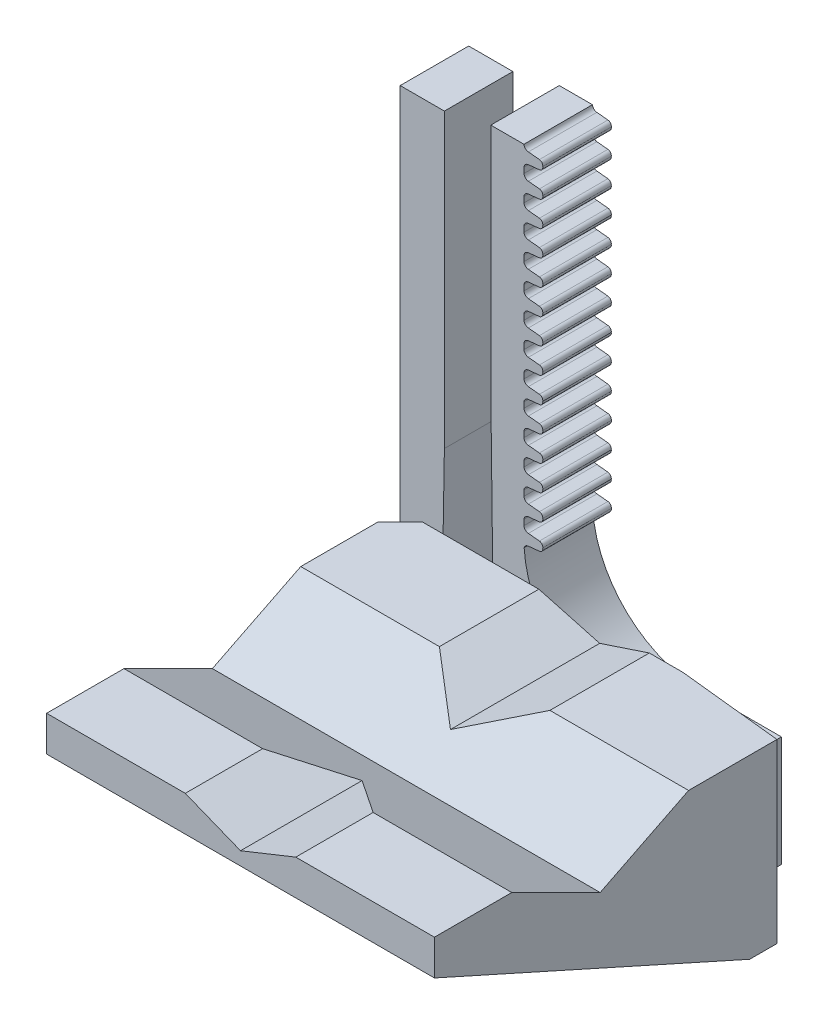
SolidWorks part; units mm, degrees
ref_plane "Front Plane" through (0, 0, 0) normal (0, 0, 1) x (1, 0, 0)
ref_plane "Top Plane" through (0, 0, 0) normal (0, 1, 0) x (1, 0, 0)
ref_plane "Right Plane" through (0, 0, 0) normal (1, 0, 0) x (0, 0, -1)
sketch "Sketch1" plane through (0, 0, 0) normal (0, 0, 1) x (1, 0, 0)
  line L1 (-28.3, 0) -> (0, 0)
  line L6 (-17.1, 20) -> (-17.1, 51)
  line L7 (-17.1, 51) -> (-20.1, 51)
  line L9 (0, 10) -> (-7.1, 10)
  line L11 (-20.1, 51) -> (-20.1, 6)
  line L12 (-28.3, 0) -> (-28.3, 50)
  line L13 (-28.3, 50) -> (-24.3, 50)
  line L14 (-24.3, 50) -> (-24.3, 6)
  line L15 (-24.3, 6) -> (-20.1, 6)
  line L16 (0, 10) -> (0, 0)
  arc A1 (-17.1, 20) -> (-7.1, 10) centre (-7.1, 20) ccw
  dimension "D8" = 10
  dimension "D1" = 45
  dimension "D2" = 4.2
  dimension "D3" = 3
  dimension "D4" = 17.1
  dimension "D5" = 50
  dimension "D6" = 6
  dimension "D7" = 10
  dimension "D9" = 4
extrude "Boss-Extrude1" add sketch "Sketch1" along normal blind 6.2
sketch "Sketch2" plane through (0, 0, 0) normal (0, -1, 0) x (1, 0, 0)
  line L0 (0, 6.2) -> (0, 10.4)
  line L1 (0, 10.4) -> (11, 10.4)
  line L2 (11, 10.4) -> (11, 42.4)
  line L3 (11, 42.4) -> (-24.1, 42.4)
  line L4 (-24.1, 42.4) -> (-24.1, 10.4)
  line L5 (-24.1, 10.4) -> (-13.1, 10.4)
  line L6 (-13.1, 10.4) -> (-13.1, 6.2)
  line L7 (-28.3, 6.2) -> (0, 6.2) construction
  line L8 (-13.1, 6.2) -> (0, 6.2)
  dimension "D1" = 4.2
  dimension "D2" = 7
  dimension "D3" = 11
  dimension "D4" = 11
  dimension "D5" = 32
extrude "Boss-Extrude2" add sketch "Sketch2" against normal blind 21
chamfer "Chamfer1" distance 5 angle 80 1 edges at (-6.55, 0, 42.4)
sketch "Sketch3" plane through (0, 0, 0) normal (1, 0, 0) x (0, 0, -1)
  line L0 (-6.2, 10) -> (-7.6, 10)
  line L1 (-7.6, 10) -> (-10.4, 21)
  line L2 (-10.4, 21) -> (-6.2, 21)
  line L3 (-6.2, 21) -> (-6.2, 10)
  dimension "D1" = 1.4
extrude "Cut-Extrude1" cut sketch "Sketch3" against normal up to next
chamfer "Chamfer2" distance 1 angle 84 1 edges at (11, 10.5, 10.4)
chamfer "Chamfer3" distance 2 angle 45 1 edges at (-24.1, 10.5, 10.4)
sketch "Sketch5" plane through (11, 0, 0) normal (1, 0, 0) x (0, 0, -1)
  line L0 (-42.4, 17.8) -> (-13.8689, 5)
  line L1 (-42.4, 21) -> (-42.4, 5) construction
  line L3 (-13.8689, 5) -> (-10.9662, -4.1087)
  line L4 (-10.9662, -4.1087) -> (-44.0369, 0.9377)
  line L5 (-44.0369, 0.9377) -> (-42.4, 17.8)
  line L6 (-11.4, 21) -> (-10.4, 21) construction
  dimension "D1" = 3.2
  dimension "D2" = 16
extrude "Cut-Extrude2" cut sketch "Sketch5" against normal up to next
sketch "Sketch6" plane through (0, 0, 10.4) normal (0, 0, -1) x (-1, 0, 0)
  line L0 (13.1, 0) -> (24.1, 5)
  line L1 (24.1, 5) -> (37.1983, 5)
  line L3 (-20.705, 5) -> (-11, 5)
  line L4 (-11, 5) -> (0, 0)
  line L5 (0, 0) -> (13.1, 0)
  line L6 (37.1983, 5) -> (28.626, -4.5222)
  line L7 (28.626, -4.5222) -> (-13.826, -5.6293)
  line L8 (-13.826, -5.6293) -> (-20.705, 5)
extrude "Cut-Extrude3" cut sketch "Sketch6" against normal up to next
sketch "Sketch7" plane through (0, 0, 6.2) normal (0, 0, 1) x (1, 0, 0)
  line L0 (-17.1, 20) -> (-17.1, 51) construction
  line L1 (-15.4, 50.1) -> (-17.4129, 50.1) construction
  line L2 (-16.7, 50.6) -> (-15.7, 50.5)
  line L3 (-16.7, 49.6) -> (-15.7, 49.7)
  line L4 (-17.1, 49.2) -> (-17.1, 48.7)
  line L5 (-16.7, 48.3) -> (-15.7, 48.2)
  line L6 (-16.7, 47.3) -> (-15.7, 47.4)
  line L7 (-17.1, 46.9) -> (-17.1, 46.4)
  line L8 (-16.7, 46) -> (-15.7, 45.9)
  line L9 (-16.7, 45) -> (-15.7, 45.1)
  line L10 (-17.1, 44.6) -> (-17.1, 44.1)
  line L11 (-16.7, 43.7) -> (-15.7, 43.6)
  line L12 (-16.7, 42.7) -> (-15.7, 42.8)
  line L13 (-17.1, 42.3) -> (-17.1, 41.8)
  line L14 (-16.7, 41.4) -> (-15.7, 41.3)
  line L15 (-16.7, 40.4) -> (-15.7, 40.5)
  line L16 (-17.1, 40) -> (-17.1, 39.5)
  line L17 (-16.7, 39.1) -> (-15.7, 39)
  line L18 (-16.7, 38.1) -> (-15.7, 38.2)
  line L19 (-17.1, 37.7) -> (-17.1, 37.2)
  line L20 (-16.7, 36.8) -> (-15.7, 36.7)
  line L21 (-16.7, 35.8) -> (-15.7, 35.9)
  line L22 (-17.1, 35.4) -> (-17.1, 34.9)
  line L23 (-16.7, 34.5) -> (-15.7, 34.4)
  line L24 (-16.7, 33.5) -> (-15.7, 33.6)
  line L25 (-17.1, 33.1) -> (-17.1, 32.6)
  line L26 (-16.7, 32.2) -> (-15.7, 32.1)
  line L27 (-16.7, 31.2) -> (-15.7, 31.3)
  line L28 (-17.1, 30.8) -> (-17.1, 30.3)
  line L29 (-16.7, 29.9) -> (-15.7, 29.8)
  line L30 (-16.7, 28.9) -> (-15.7, 29)
  line L31 (-17.1, 28.5) -> (-17.1, 28)
  line L32 (-16.7, 27.6) -> (-15.7, 27.5)
  line L33 (-16.7, 26.6) -> (-15.7, 26.7)
  line L34 (-17.1, 26.2) -> (-17.1, 25.7)
  line L35 (-16.7, 25.3) -> (-15.7, 25.2)
  line L36 (-16.7, 24.3) -> (-15.7, 24.4)
  line L37 (-17.1, 23.9) -> (-17.1, 23.4)
  line L38 (-16.7, 23) -> (-15.7, 22.9)
  line L39 (-16.7, 22) -> (-15.7, 22.1)
  line L40 (-17.1, 21.6) -> (-17.1, 21.1)
  line L41 (-16.7, 20.7) -> (-15.7, 20.6)
  line L42 (-16.7, 19.7) -> (-15.7, 19.8)
  line L43 (-17.1, 19.3) -> (-17.1, 18.8)
  line L44 (-17.1, 18.8) -> (-18.685, 49.2)
  line L45 (-18.685, 49.2) -> (-17.1, 51)
  arc A0 (-17.1, 51) -> (-16.7, 50.6) centre (-16.6556, 51.0444) ccw
  arc A1 (-15.7, 50.5) -> (-15.4, 50.1) centre (-15.7338, 50.1622) cw
  arc A2 (-17.1, 49.2) -> (-16.7, 49.6) centre (-16.6556, 49.1556) cw
  arc A3 (-15.7, 49.7) -> (-15.4, 50.1) centre (-15.7338, 50.0378) ccw
  arc A4 (-17.1, 48.7) -> (-16.7, 48.3) centre (-16.6556, 48.7444) ccw
  arc A5 (-15.7, 48.2) -> (-15.4, 47.8) centre (-15.7338, 47.8622) cw
  arc A6 (-17.1, 46.9) -> (-16.7, 47.3) centre (-16.6556, 46.8556) cw
  arc A7 (-15.7, 47.4) -> (-15.4, 47.8) centre (-15.7338, 47.7378) ccw
  arc A8 (-17.1, 46.4) -> (-16.7, 46) centre (-16.6556, 46.4444) ccw
  arc A9 (-15.7, 45.9) -> (-15.4, 45.5) centre (-15.7338, 45.5622) cw
  arc A10 (-17.1, 44.6) -> (-16.7, 45) centre (-16.6556, 44.5556) cw
  arc A11 (-15.7, 45.1) -> (-15.4, 45.5) centre (-15.7338, 45.4378) ccw
  arc A12 (-17.1, 44.1) -> (-16.7, 43.7) centre (-16.6556, 44.1444) ccw
  arc A13 (-15.7, 43.6) -> (-15.4, 43.2) centre (-15.7338, 43.2622) cw
  arc A14 (-17.1, 42.3) -> (-16.7, 42.7) centre (-16.6556, 42.2556) cw
  arc A15 (-15.7, 42.8) -> (-15.4, 43.2) centre (-15.7338, 43.1378) ccw
  arc A16 (-17.1, 41.8) -> (-16.7, 41.4) centre (-16.6556, 41.8444) ccw
  arc A17 (-15.7, 41.3) -> (-15.4, 40.9) centre (-15.7338, 40.9622) cw
  arc A18 (-17.1, 40) -> (-16.7, 40.4) centre (-16.6556, 39.9556) cw
  arc A19 (-15.7, 40.5) -> (-15.4, 40.9) centre (-15.7338, 40.8378) ccw
  arc A20 (-17.1, 39.5) -> (-16.7, 39.1) centre (-16.6556, 39.5444) ccw
  arc A21 (-15.7, 39) -> (-15.4, 38.6) centre (-15.7338, 38.6622) cw
  arc A22 (-17.1, 37.7) -> (-16.7, 38.1) centre (-16.6556, 37.6556) cw
  arc A23 (-15.7, 38.2) -> (-15.4, 38.6) centre (-15.7338, 38.5378) ccw
  arc A24 (-17.1, 37.2) -> (-16.7, 36.8) centre (-16.6556, 37.2444) ccw
  arc A25 (-15.7, 36.7) -> (-15.4, 36.3) centre (-15.7338, 36.3622) cw
  arc A26 (-17.1, 35.4) -> (-16.7, 35.8) centre (-16.6556, 35.3556) cw
  arc A27 (-15.7, 35.9) -> (-15.4, 36.3) centre (-15.7338, 36.2378) ccw
  arc A28 (-17.1, 34.9) -> (-16.7, 34.5) centre (-16.6556, 34.9444) ccw
  arc A29 (-15.7, 34.4) -> (-15.4, 34) centre (-15.7338, 34.0622) cw
  arc A30 (-17.1, 33.1) -> (-16.7, 33.5) centre (-16.6556, 33.0556) cw
  arc A31 (-15.7, 33.6) -> (-15.4, 34) centre (-15.7338, 33.9378) ccw
  arc A32 (-17.1, 32.6) -> (-16.7, 32.2) centre (-16.6556, 32.6444) ccw
  arc A33 (-15.7, 32.1) -> (-15.4, 31.7) centre (-15.7338, 31.7622) cw
  arc A34 (-17.1, 30.8) -> (-16.7, 31.2) centre (-16.6556, 30.7556) cw
  arc A35 (-15.7, 31.3) -> (-15.4, 31.7) centre (-15.7338, 31.6378) ccw
  arc A36 (-17.1, 30.3) -> (-16.7, 29.9) centre (-16.6556, 30.3444) ccw
  arc A37 (-15.7, 29.8) -> (-15.4, 29.4) centre (-15.7338, 29.4622) cw
  arc A38 (-17.1, 28.5) -> (-16.7, 28.9) centre (-16.6556, 28.4556) cw
  arc A39 (-15.7, 29) -> (-15.4, 29.4) centre (-15.7338, 29.3378) ccw
  arc A40 (-17.1, 28) -> (-16.7, 27.6) centre (-16.6556, 28.0444) ccw
  arc A41 (-15.7, 27.5) -> (-15.4, 27.1) centre (-15.7338, 27.1622) cw
  arc A42 (-17.1, 26.2) -> (-16.7, 26.6) centre (-16.6556, 26.1556) cw
  arc A43 (-15.7, 26.7) -> (-15.4, 27.1) centre (-15.7338, 27.0378) ccw
  arc A44 (-17.1, 25.7) -> (-16.7, 25.3) centre (-16.6556, 25.7444) ccw
  arc A45 (-15.7, 25.2) -> (-15.4, 24.8) centre (-15.7338, 24.8622) cw
  arc A46 (-17.1, 23.9) -> (-16.7, 24.3) centre (-16.6556, 23.8556) cw
  arc A47 (-15.7, 24.4) -> (-15.4, 24.8) centre (-15.7338, 24.7378) ccw
  arc A48 (-17.1, 23.4) -> (-16.7, 23) centre (-16.6556, 23.4444) ccw
  arc A49 (-15.7, 22.9) -> (-15.4, 22.5) centre (-15.7338, 22.5622) cw
  arc A50 (-17.1, 21.6) -> (-16.7, 22) centre (-16.6556, 21.5556) cw
  arc A51 (-15.7, 22.1) -> (-15.4, 22.5) centre (-15.7338, 22.4378) ccw
  arc A52 (-17.1, 21.1) -> (-16.7, 20.7) centre (-16.6556, 21.1444) ccw
  arc A53 (-15.7, 20.6) -> (-15.4, 20.2) centre (-15.7338, 20.2622) cw
  arc A54 (-17.1, 19.3) -> (-16.7, 19.7) centre (-16.6556, 19.2556) cw
  arc A55 (-15.7, 19.8) -> (-15.4, 20.2) centre (-15.7338, 20.1378) ccw
  dimension "D1" = 0.4
  dimension "D6" = 0.4
  dimension "D2" = 0.3
  dimension "D3" = 0.4
  dimension "D4" = 0.1
  dimension "D5" = 1
  dimension "D7" = 14
extrude "Boss-Extrude3" add sketch "Sketch7" against normal up to surface (6.2 mm away) up to face at (-17.161, 22.9026, 0)
sketch "Sketch8" plane through (11, 0, 0) normal (1, 0, 0) x (0, 0, -1)
  line L0 (-35.4, 21) -> (-27.4, 17)
  line L1 (-11.4, 21) -> (-42.4, 21) construction
  line L2 (-27.4, 17) -> (-19.4, 21)
  line L3 (-19.4, 21) -> (-35.4, 21)
  line L4 (-42.4, 21) -> (-42.4, 17.8) construction
  dimension "D1" = 4
  dimension "D2" = 16
  dimension "D3" = 7
  dimension "D4" = 8
extrude "Cut-Extrude4" cut sketch "Sketch8" against normal up to next
sketch "Sketch10" plane through (0, 0, 42.4) normal (0, 0, 1) x (1, 0, 0)
  line L0 (-11.55, 21) -> (-6.55, 19)
  line L1 (11, 21) -> (-24.1, 21) construction
  line L2 (-6.55, 19) -> (-1.55, 21)
  line L3 (-1.55, 21) -> (-11.55, 21)
  dimension "D1" = 10
  dimension "D2" = 5
  dimension "D3" = 2
  dimension "D4" = 12.55
extrude "Cut-Extrude5" cut sketch "Sketch10" against normal through all
sketch "Sketch11" plane through (0, 0, 0) normal (0, 0, -1) x (-1, 0, 0)
  line L0 (24.3, 23.55) -> (24.6, 5.974)
  line L1 (24.3, 6) -> (24.3, 50) construction
  line L2 (24.6, 5.974) -> (19.8, 5.974)
  line L3 (19.8, 5.974) -> (20.1, 30.2438)
  line L4 (20.1, 51) -> (20.1, 6) construction
  line L5 (20.1, 30.2438) -> (24.3, 23.55)
  point P8 (19.6884, 5.9964)
  point P9 (20.1, 30.2438)
  point P10 (24.3, 23.55)
  point P11 (19.394, 5.974)
  dimension "D1" = 4.8
  dimension "D2" = 0.3
extrude "Cut-Extrude6" cut sketch "Sketch11" against normal up to next
equation "\"D4@Sketch8\"=\"D2@Sketch8\"/2"
equation "\"D4@Sketch10\"=(35.10-\"D1@Sketch10\")/2"
equation "\"D2@Sketch10\"=\"D1@Sketch10\"/2"
